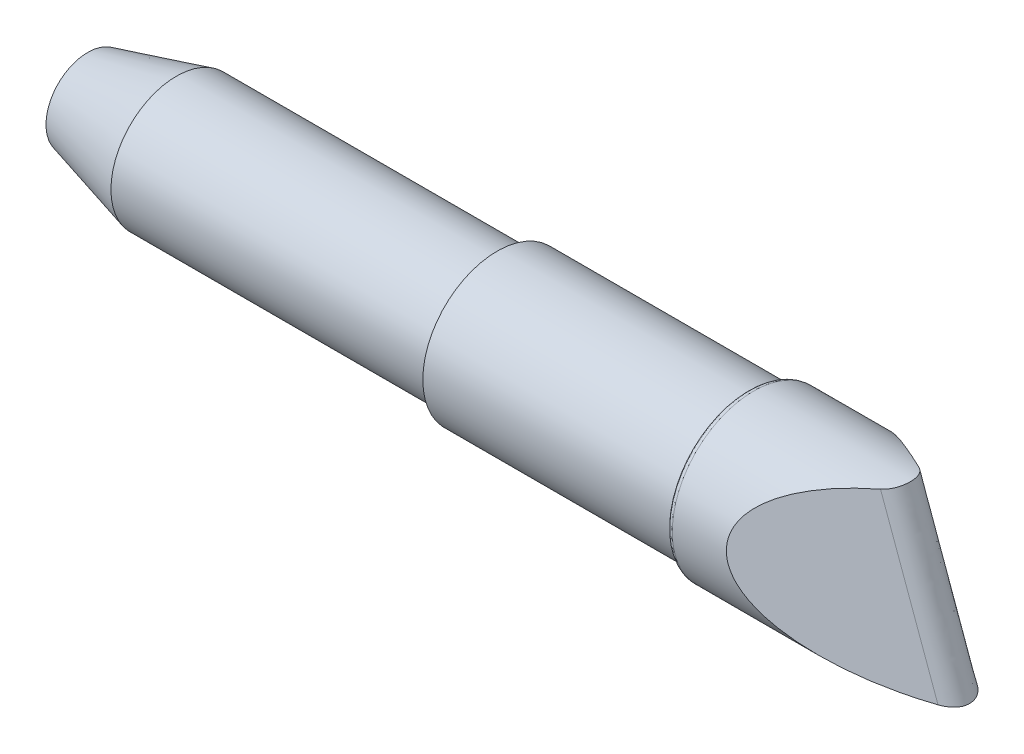
SolidWorks part; units mm, degrees
ref_plane "Plano frontal" through (0, 0, 0) normal (0, 0, 1) x (1, 0, 0)
ref_plane "Plano superior" through (0, 0, 0) normal (0, 1, 0) x (1, 0, 0)
ref_plane "Plano direito" through (0, 0, 0) normal (1, 0, 0) x (0, 0, -1)
sketch "Esboço1" plane through (0, 0, 0) normal (0, 0, 1) x (1, 0, 0)
  line L0 (0, 0) -> (34.7806, 0) construction
  line L1 (0, 0) -> (0, 1.335)
  line L2 (0, 1.335) -> (2.8364, 2.095)
  line L3 (2.8364, 2.095) -> (13.09, 2.095)
  line L4 (13.09, 2.095) -> (13.09, 2.375)
  line L5 (13.09, 2.375) -> (21.09, 2.375)
  line L6 (21.09, 2.375) -> (21.09, 2.6)
  line L7 (0, 0) -> (28.2, 0)
  line L8 (22.4692, 2.6) -> (28.2, 2.6)
  line L9 (21.09, 2.6) -> (22.4692, 2.6)
  line L10 (28.2, 2.6) -> (28.2, 0)
  arc A0 (22.4692, 2.6) -> (27.9396, 0.5682) centre (22.4692, -5.78) cw construction
  arc A1 (27.9396, 0.5682) -> (28.2, 0) centre (27.45, 0) cw construction
  dimension "D9" = 8.38
  dimension "D5" = 0.75
  dimension "D12" = 5.78
  dimension "D13" = 5.7308
  dimension "D18" = 1.3792
  dimension "D2" = 2.8364
  dimension "D3" = 10.2536
  dimension "D4" = 8
  dimension "D6" = 4.19
  dimension "D7" = 4.75
  dimension "D8" = 5.2
  dimension "D10" = 15
  dimension "D11" = 1.3792
  dimension "D14" = 7.11
  dimension "D15" = 28.2
  dimension "D16" = 21.09
  dimension "D17" = 2.67
revolve "Revolução1" add sketch "Esboço1" angle 360 about L0
sketch "Esboço2" plane through (0, 0, 0) normal (0, 0, 1) x (1, 0, 0)
  line L3 (28.2, -2.6) -> (25.9434, 3.6)
  line L8 (25.9434, 3.6) -> (29, 3.6)
  line L9 (29, 3.6) -> (29, -2.6)
  line L10 (29, -2.6) -> (28.2, -2.6)
  line L11 (28.2, -2.6) -> (28.2, 2.6) construction
  line L12 (28.2, 2.6) -> (21.09, 2.6) construction
  dimension "D1" = 20
  dimension "D2" = 1
  dimension "D4" = 0.8
extrude "Corte-extrusão1" cut sketch "Esboço2" against normal mid plane 10
ref_plane "Plano1" through (28.2, -2.6, 0) normal (0, -1, 0) x (-1, 0, 0)
sketch "Esboço3" plane through (-3.8636, -2.6, 0) normal (0, 1, 0) x (0, 0, 1)
  line L0 (0.4619, 31.98) -> (4.0777, 25.0636) construction
  line L1 (-4.0777, 25.0636) -> (-0.612, 31.6929)
  line L2 (0, 32.0636) -> (0, 7.504) construction
  line L3 (0.612, 31.6929) -> (4.0777, 25.0636)
  line L4 (0.4619, 31.98) -> (0, 32.8635) construction
  line L5 (0, 32.8635) -> (-0.4619, 31.98) construction
  line L6 (-0.4619, 31.98) -> (-4.0777, 25.0636) construction
  line L7 (0, 29.8069) -> (0, 32.8636) construction
  arc A0 (4.0777, 25.0636) -> (-4.0777, 25.0636) centre (0, 32.8635) ccw
  arc A1 (-0.612, 31.6929) -> (0.612, 31.6929) centre (0, 31.373) cw
  dimension "D1" = 0.9238
  dimension "D4" = 7
  dimension "D2" = 55.2
  dimension "D3" = 0.8
extrude "Corte-extrusão2" cut sketch "Esboço3" along direction (-0.342, 0.9397, 0) on the side of the normal blind 10
fillet "Filete1" radius 0.2 1 edges at (21.09, 0, 2.6)
